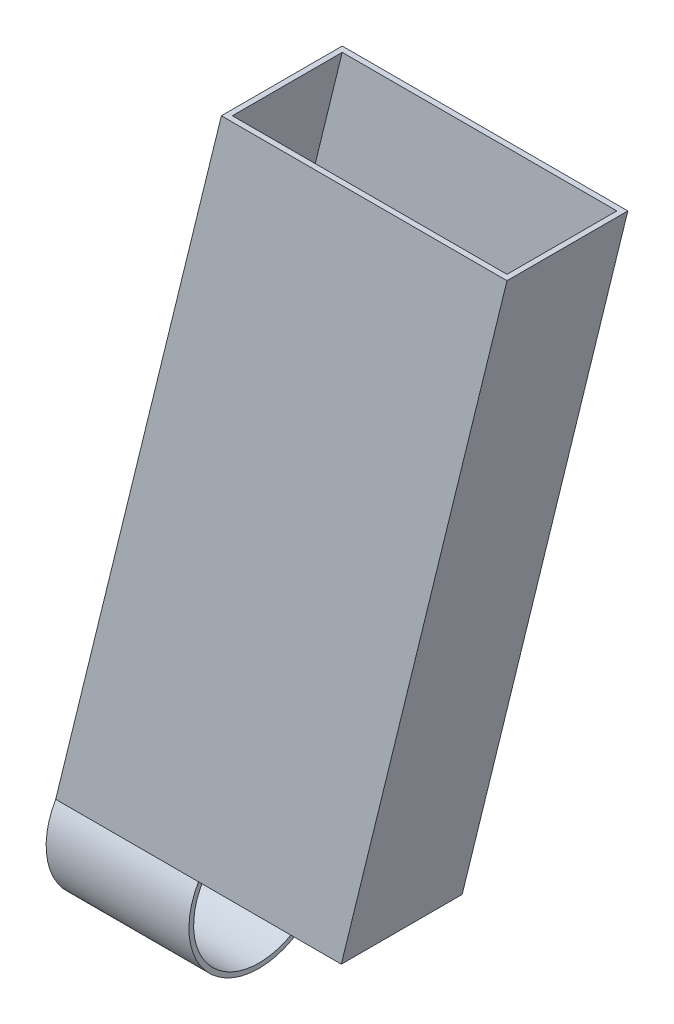
SolidWorks part; units mm, degrees
ref_plane "前视基准面" through (0, 0, 0) normal (0, 0, 1) x (1, 0, 0)
ref_plane "上视基准面" through (0, 0, 0) normal (0, 1, 0) x (1, 0, 0)
ref_plane "右视基准面" through (0, 0, 0) normal (1, 0, 0) x (0, 0, -1)
sketch "草图1" plane through (0, 0, 0) normal (0, 1, 0) x (1, 0, 0)
  line L1 (-12.5, 5) -> (12.5, 5)
  line L2 (-12.5, 5) -> (-12.5, -5)
  line L3 (-12.5, -5) -> (12.5, -5)
  line L4 (12.5, 5) -> (12.5, -5)
  line L5 (-12.5, 5) -> (12.5, -5) construction
  line L6 (-12.5, -5) -> (12.5, 5) construction
  line L7 (-13, 5.5) -> (13, 5.5)
  line L8 (-13, 5.5) -> (-13, -5.5)
  line L9 (-13, -5.5) -> (13, -5.5)
  line L10 (13, 5.5) -> (13, -5.5)
  line L11 (-13, 5.5) -> (13, -5.5) construction
  line L12 (-13, -5.5) -> (13, 5.5) construction
  point P0 (0, 0)
  point P7 (0, 0)
sketch "草图2" plane through (0, 0, 0) normal (0, 0, 1) x (1, 0, 0)
  line L0 (0, 0) -> (15.0814, 61.4271)
sketch3d "3D草图1"
  line L0 (0, 0, 0) -> (15.0814, 61.4271, 0) construction
  line L1 (0, 0, 0) -> (15.0814, 61.4271, 0)
sweep "扫描1" add profiles "草图1" path "草图2"
sketch "草图3" plane through (0, 0, 0) normal (1, 0, 0) x (0, 0, -1)
  line L0 (-5.5, 0) -> (5.5, 0) construction
  line L1 (-5.5, 0) -> (-5, 0)
  line L2 (5, 0) -> (5.5, 0)
  arc A0 (-5, 0) -> (5, 0) centre (0, -3.2154) ccw
  arc A1 (-5.5, 0) -> (5.5, 0) centre (0, -3.2154) ccw
  point P9 (0, -4.7988)
  point P10 (0, -3.2154)
extrude "凸台-拉伸1" add sketch "草图3" against normal blind 13
